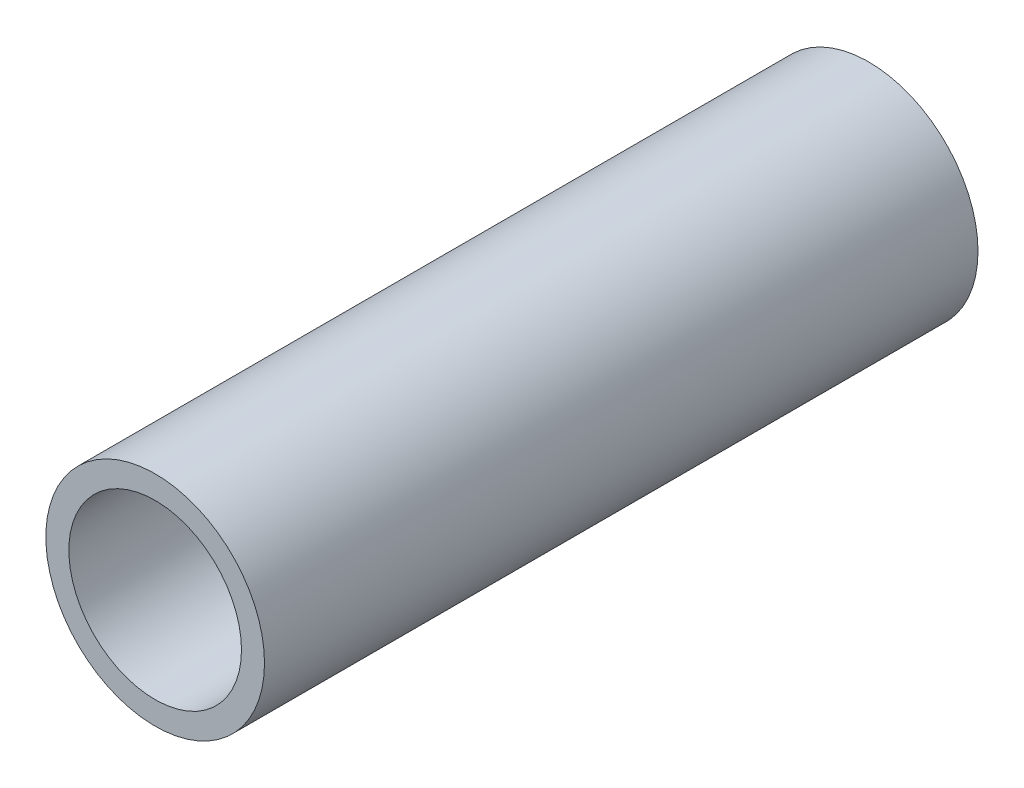
SolidWorks part; units mm, degrees
ref_plane "Alzado" through (0, 0, 0) normal (0, 0, 1) x (1, 0, 0)
ref_plane "Planta" through (0, 0, 0) normal (0, 1, 0) x (1, 0, 0)
ref_plane "Vista lateral" through (0, 0, 0) normal (1, 0, 0) x (0, 0, -1)
sketch "Croquis1" plane through (0, 0, 0) normal (0, 0, 1) x (1, 0, 0)
  circle A0 centre (0, 0) radius 9.5
  circle A1 centre (0, 0) radius 7.5
  dimension "D1" = 19
  dimension "D2" = 15
extrude "Saliente-Extruir1" add sketch "Croquis1" along normal blind 62
